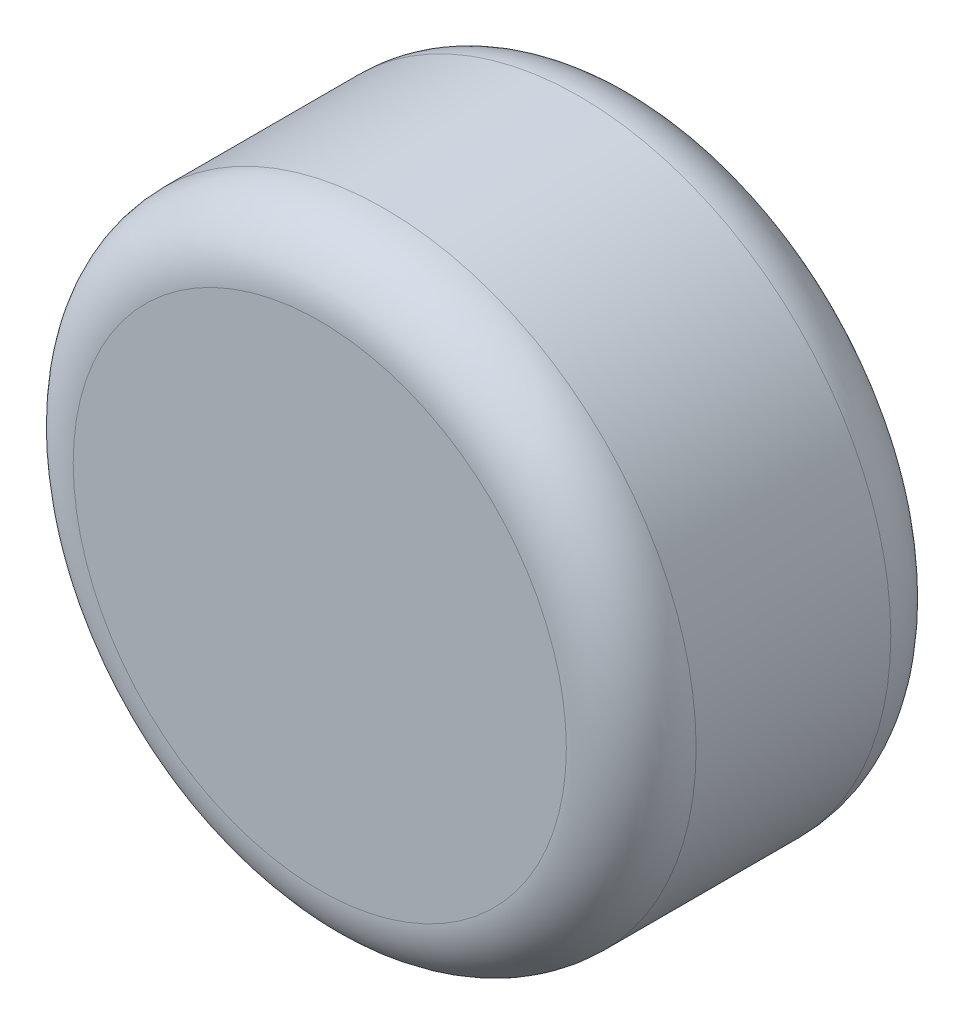
SolidWorks part; units mm, degrees
ref_plane "正面" through (0, 0, 0) normal (0, 0, 1) x (1, 0, 0)
ref_plane "平面" through (0, 0, 0) normal (0, 1, 0) x (1, 0, 0)
ref_plane "右側面" through (0, 0, 0) normal (1, 0, 0) x (0, 0, -1)
sketch "ｽｹｯﾁ1" plane through (0, 0, 0) normal (0, 0, 1) x (1, 0, 0)
  circle A0 centre (0, 0) radius 24
  dimension "D1" = 48
extrude "ﾎﾞｽ - 押し出し1" add sketch "ｽｹｯﾁ1" along normal blind 25
fillet "ﾌｨﾚｯﾄ1" radius 5 2 edges at (24, 0, 0) (24, 0, 25)
